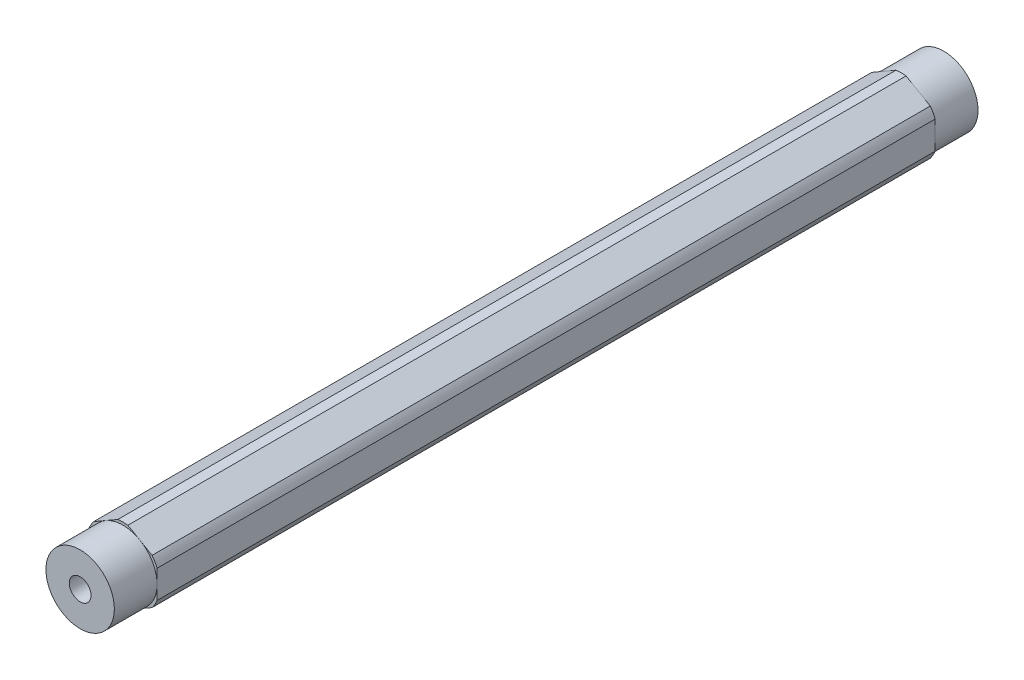
SolidWorks part; units mm, degrees
ref_plane "Front Plane" through (0, 0, 0) normal (0, 0, 1) x (1, 0, 0)
ref_plane "Top Plane" through (0, 0, 0) normal (0, 1, 0) x (1, 0, 0)
ref_plane "Right Plane" through (0, 0, 0) normal (1, 0, 0) x (0, 0, -1)
sketch "Sketch1" plane through (0, 0, 0) normal (0, 0, 1) x (1, 0, 0)
  line L1 (0, 7.3323) -> (-6.35, 3.6662)
  line L2 (-6.35, 3.6662) -> (-6.35, -3.6662)
  line L3 (-6.35, -3.6662) -> (0, -7.3323)
  line L4 (0, -7.3323) -> (6.35, -3.6662)
  line L5 (6.35, -3.6662) -> (6.35, 3.6662)
  line L6 (6.35, 3.6662) -> (0, 7.3323)
  circle A0 centre (0, 0) radius 6.35 construction
  circle A1 centre (0, 0) radius 6.858
  circle A2 centre (0, 0) radius 2.0193
  dimension "D1" = 12.7
  dimension "D2" = 13.716
  dimension "D3" = 4.0386
extrude "Boss-Extrude1" add sketch "Sketch1" along normal mid plane 144.4625 contours L5 A1 L6 L1 L2 L3 L4
sketch "Sketch2" plane through (0, 0, 72.2313) normal (0, 0, 1) x (1, 0, 0)
  circle A0 centre (0, 0) radius 6.35
  circle A1 centre (0, 0) radius 2.0193
  dimension "D1" = 12.7
  dimension "D2" = 4.0386
extrude "Boss-Extrude2" add sketch "Sketch2" along normal blind 7.9375
mirror "Mirror1" about plane through (0, 0, 0) normal (0, 0, 1) of "Boss-Extrude2"
